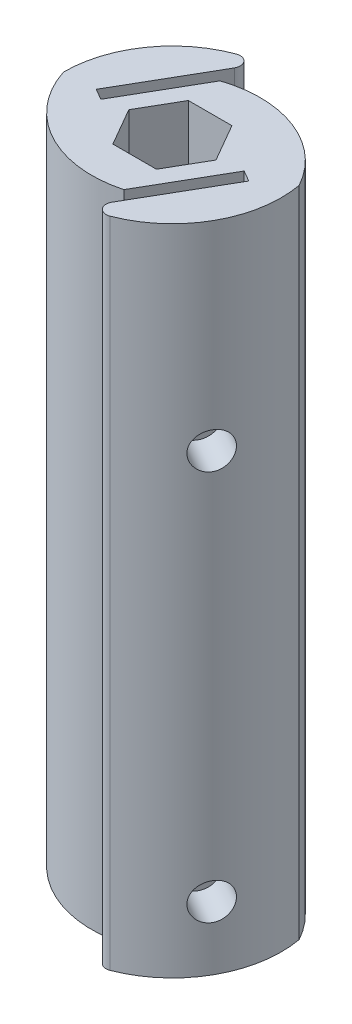
SolidWorks part; units mm, degrees
ref_plane "Front Plane" through (0, 0, 0) normal (0, 0, 1) x (1, 0, 0)
ref_plane "Top Plane" through (0, 0, 0) normal (0, 1, 0) x (1, 0, 0)
ref_plane "Right Plane" through (0, 0, 0) normal (1, 0, 0) x (0, 0, -1)
sketch "Sketch1" plane through (0, 0, 0) normal (0, 1, 0) x (1, 0, 0)
  line L0 (4.053, -12.538) -> (11.755, 0.8022)
  line L1 (3.8128, -6.604) -> (7.6256, 0)
  line L2 (7.6256, 0) -> (3.8128, 6.604)
  line L3 (3.8128, 6.604) -> (-3.8128, 6.604)
  line L4 (-3.8128, 6.604) -> (-7.6256, 0)
  line L5 (-7.6256, 0) -> (-3.8128, -6.604)
  line L6 (-3.8128, -6.604) -> (3.8128, -6.604)
  line L7 (13.6797, -0.309) -> (11.755, 0.8022)
  line L8 (13.6797, -0.309) -> (4.91, -15.4986)
  line L9 (-4.0149, 12.35) -> (-11.645, -0.8657)
  line L10 (-13.5697, 0.2455) -> (-4.7223, 15.5698)
  line L11 (-11.645, -0.8657) -> (-13.5697, 0.2455)
  circle A0 centre (0, 0) radius 6.604 construction
  arc A1 (-6.6514, 17.8511) -> (-19.05, 0) centre (0, 0) ccw
  arc A2 (4.91, -15.4986) -> (6.8562, -17.7734) centre (6.2849, -16.2923) ccw
  arc A3 (-4.7223, 15.5698) -> (-6.6514, 17.8511) centre (-6.0971, 16.3635) ccw
  arc A4 (-4.0149, 12.35) -> (18.7347, 3.4516) centre (2.0345, -5.714) cw
  arc A5 (6.8562, -17.7734) -> (18.7347, 3.4516) centre (0, 0) ccw
  arc A6 (4.053, -12.538) -> (-19.05, 0) centre (-0.9208, 5.8512) cw
  point P11 (5.7192, -3.302)
  point P20 (0.055, -0.0318)
  dimension "D2" = 38.1
  dimension "D3" = 2.2225
  dimension "D4" = 3.175
  dimension "D7" = 3.175
  dimension "D10" = 19.05
  dimension "D1" = 13.208
  dimension "D5" = 2
  dimension "D6" = 6.5722
extrude "Boss-Extrude1" add sketch "Sketch1" along normal blind 114.3
sketch "Sketch2" plane through (5.7192, 0, 3.302) normal (-0.866, 0, -0.5) x (-0.5, 0, 0.866)
  line L0 (3.8128, 0) -> (-3.8128, 0) construction
  circle A0 centre (0, 11.1125) radius 3.175
  circle A1 centre (0, 79.4385) radius 3.175
  point P6 (0, 0)
  dimension "D1" = 6.35
  dimension "D2" = 11.1125
  dimension "D3" = 68.326
extrude "Cut-Extrude1" cut sketch "Sketch2" against normal through all and the other way through all
